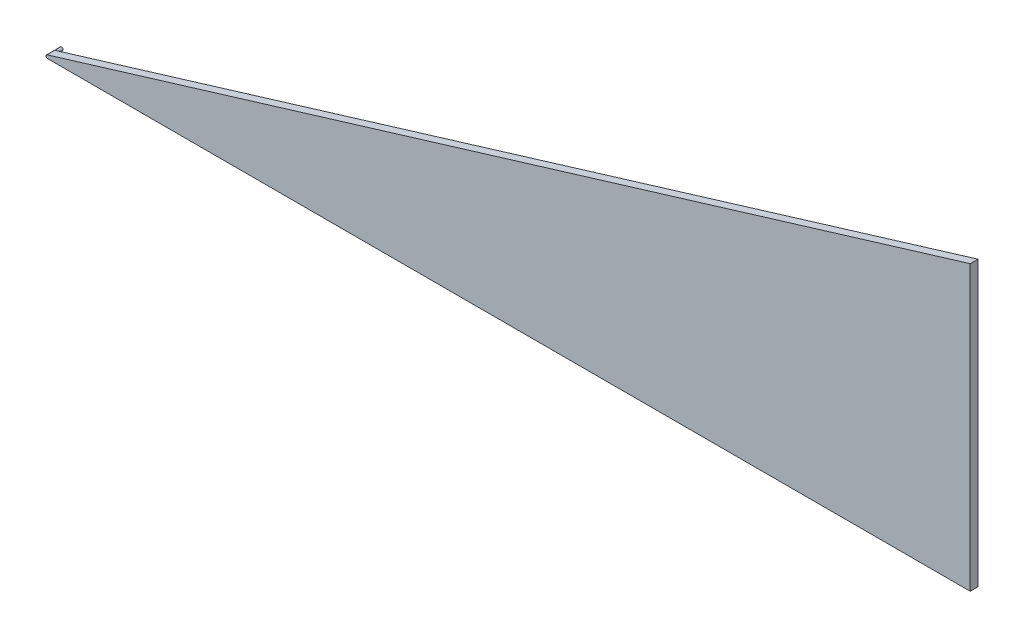
SolidWorks part; units mm, degrees
ref_plane "Front" through (0, 0, 0) normal (0, 0, 1) x (1, 0, 0)
ref_plane "Top" through (0, 0, 0) normal (0, 1, 0) x (1, 0, 0)
ref_plane "Right" through (0, 0, 0) normal (1, 0, 0) x (0, 0, -1)
sketch "草图1" plane through (0, 0, 0) normal (0, 0, 1) x (1, 0, 0)
  circle A0 centre (0, 0) radius 20
extrude "凸台-拉伸1" add sketch "草图1" along normal blind 80
sketch "草图2" plane through (0, 0, 80) normal (0, 0, 1) x (1, 0, 0)
  line L1 (-5.8183, 19.135) -> (11858.299, 3626.6086)
  line L3 (0, -20) -> (11858.299, -20)
  line L4 (11858.299, 3626.6086) -> (11858.299, -20)
  circle A3 centre (0, 0) radius 20
  arc A4 (-5.8183, 19.135) -> (0, -20) centre (0, 0) ccw
  point P6 (-20, 0)
  dimension "D1" = 0
extrude "凸台-拉伸2" add sketch "草图2" along normal blind 100
sketch "草图4" plane through (0, 0, 0) normal (0, 0, -1) x (-1, 0, 0)
  point P0 (0, 0)
